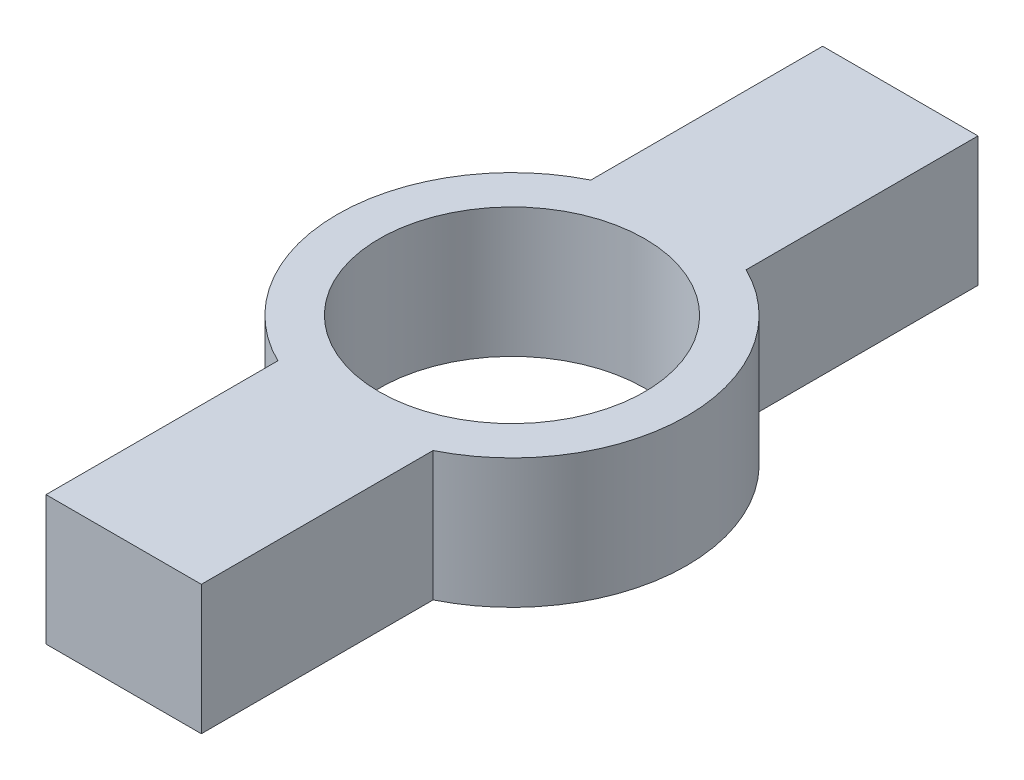
SolidWorks part; units mm, degrees
ref_plane "前视基准面" through (0, 0, 0) normal (0, 0, 1) x (1, 0, 0)
ref_plane "上视基准面" through (0, 0, 0) normal (0, 1, 0) x (1, 0, 0)
ref_plane "右视基准面" through (0, 0, 0) normal (1, 0, 0) x (0, 0, -1)
other "Configuration Table"
sketch "草图1" plane through (0, 0, 0) normal (0, 1, 0) x (1, 0, 0)
  circle A0 centre (0, 0) radius 13.5
  dimension "D1" = 27
extrude "凸台-拉伸1" add sketch "草图1" along normal blind 10
sketch "草图2" plane through (0, 10, 0) normal (0, 1, 0) x (1, 0, 0)
  line L0 (0, 0) -> (0, 13.5) construction
  line L1 (0, 0) -> (0, -13.5) construction
  line L3 (-6, 30) -> (6, 30)
  line L4 (-6, 30) -> (-6, -30)
  line L5 (-6, -30) -> (6, -30)
  line L6 (6, 30) -> (6, -30)
  circle A0 centre (0, 0) radius 13.5 construction
  dimension "D1" = 12
  dimension "D2" = 6
  dimension "D3" = 60
  dimension "D4" = 30
extrude "凸台-拉伸2" add sketch "草图2" against normal blind 10
sketch "草图3" plane through (0, 10, 0) normal (0, 1, 0) x (1, 0, 0)
  circle A0 centre (0, 0) radius 10.25
  dimension "D1" = 20.5
extrude "切除-拉伸1" cut sketch "草图3" against normal blind 10
